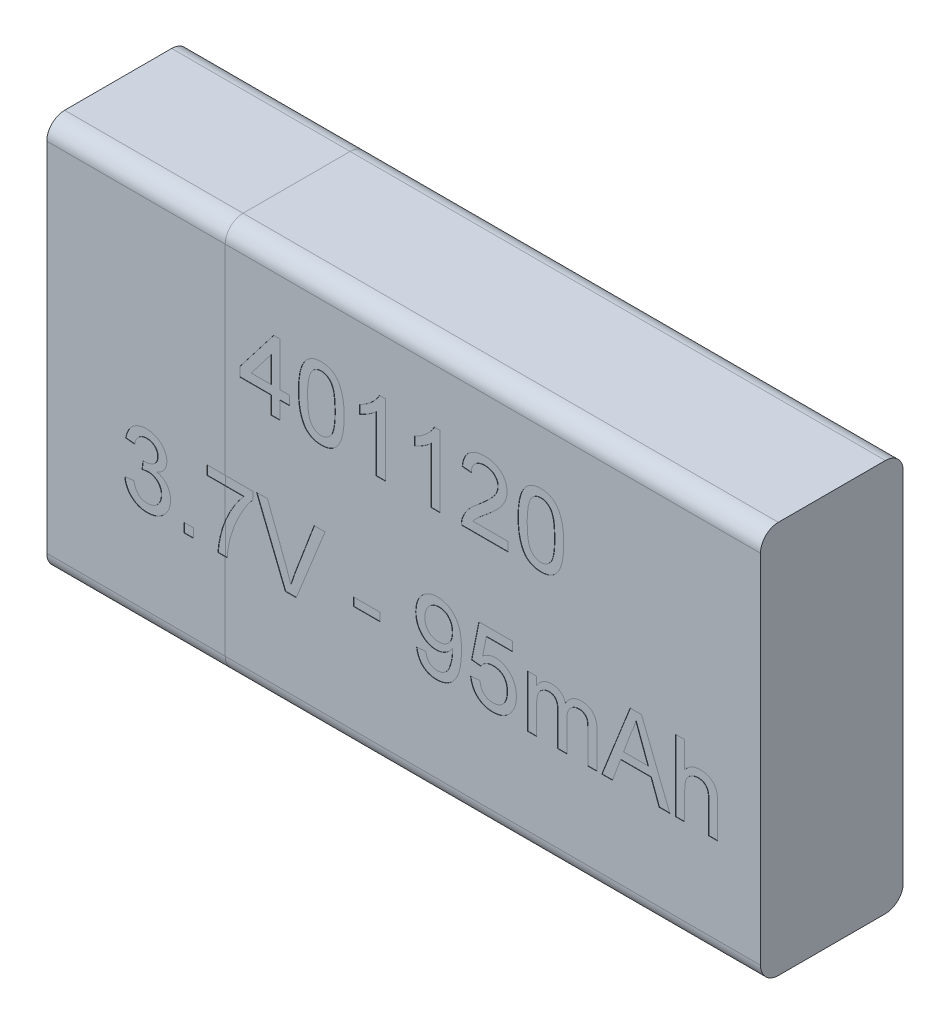
SolidWorks part; units mm, degrees
ref_plane "Plan de face" through (0, 0, 0) normal (0, 0, 1) x (1, 0, 0)
ref_plane "Plan de dessus" through (0, 0, 0) normal (0, 1, 0) x (1, 0, 0)
ref_plane "Plan de droite" through (0, 0, 0) normal (1, 0, 0) x (0, 0, -1)
sketch "Sketch1" plane through (0, 0, 0) normal (0, 0, 1) x (1, 0, 0)
  line L1 (10, -5.5) -> (-10, -5.5)
  line L2 (10, -5.5) -> (10, 5.5)
  line L3 (10, 5.5) -> (-10, 5.5)
  line L4 (-10, -5.5) -> (-10, 5.5)
  line L5 (10, -5.5) -> (-10, 5.5) construction
  line L6 (10, 5.5) -> (-10, -5.5) construction
  point P0 (0, 0)
  dimension "D1" = 11
  dimension "D2" = 20
extrude "Boss-Extrude1" add sketch "Sketch1" along normal blind 4
fillet "Fillet1" radius 0.5 4 edges at (0, -5.5, 0) (0, -5.5, 4) (0, 5.5, 4) (0, 5.5, 0)
ref_plane "Plane1" through (-5, 0, 0) normal (-1, 0, 0) x (0, 0, 1)
split "Split1" trim tools "Plane1" bodies to split 101 resulting bodies 106 107
sketch "Sketch5" plane through (0, 0, 4) normal (0, 0, 1) x (1, 0, 0)
  line L1 (-7.9429, -2.5072) -> (7.9429, -2.5072) construction
  line L2 (-7.9429, -2.5072) -> (-7.9429, 1.4928) construction
  line L3 (-7.9429, 1.4928) -> (7.9429, 1.4928) construction
  line L4 (7.9429, -2.5072) -> (7.9429, 1.4928) construction
  line L5 (-7.9429, -2.5072) -> (7.9429, 1.4928) construction
  line L6 (-7.9429, 1.4928) -> (7.9429, -2.5072) construction
  text T0 "401120\r\n3.7V - 95mAh" font "Arial" height 2
  point P8 (0, -0.5072)
  dimension "D1" = 4
extrude "Cut-Extrude1" cut sketch "Sketch5" against normal blind 0.01
